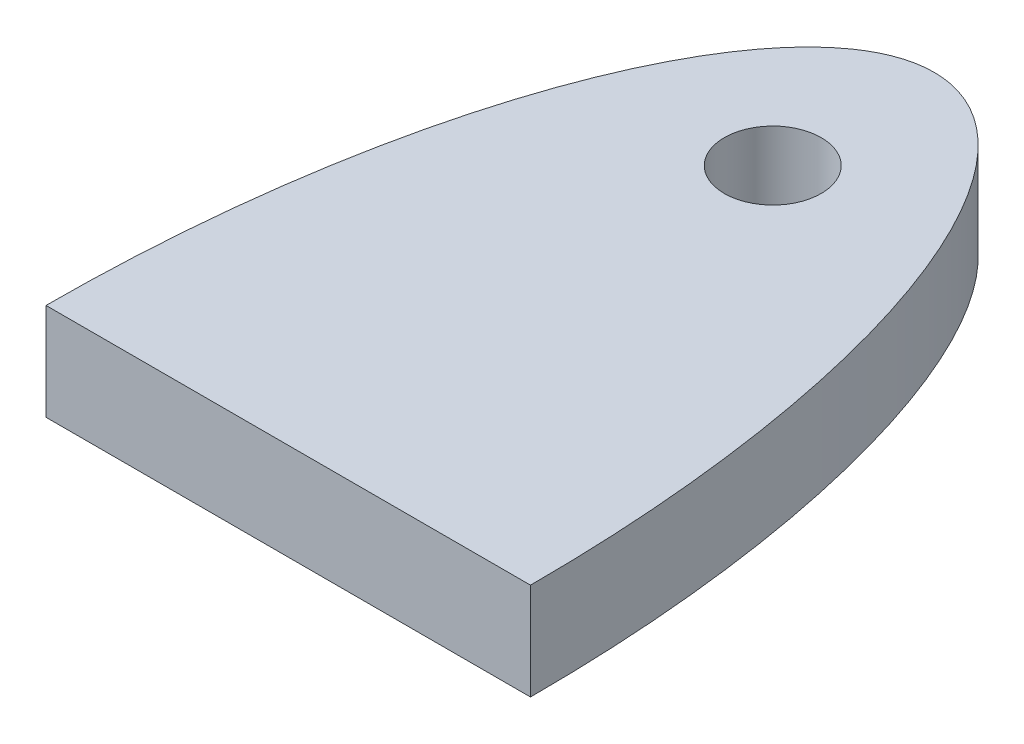
SolidWorks part; units mm, degrees
ref_plane "Front Plane" through (0, 0, 0) normal (0, 0, 1) x (1, 0, 0)
ref_plane "Top Plane" through (0, 0, 0) normal (0, 1, 0) x (1, 0, 0)
ref_plane "Right Plane" through (0, 0, 0) normal (1, 0, 0) x (0, 0, -1)
sketch "Sketch1" plane through (0, 0, 0) normal (0, 1, 0) x (1, 0, 0)
  line L1 (0, 0) -> (15, 0)
  ellipse E0 centre (7.5, 0) end of major axis (7.5, 20) minor radius 7.5 (15, 0) -> (0, 0) ccw
  dimension "D1" = 15
  dimension "D2" = 20
extrude "Boss-Extrude1" add sketch "Sketch1" along normal blind 3
sketch "Sketch2" plane through (0, 3, 0) normal (0, 1, 0) x (1, 0, 0)
  line L0 (0, 0) -> (15, 0) construction
  circle A0 centre (7.5, 15) radius 1.5
  point P2 (0, 0)
  point P5 (7.5, 0)
  dimension "D1" = 15
extrude "Cut-Extrude1" cut sketch "Sketch2" against normal blind 3
